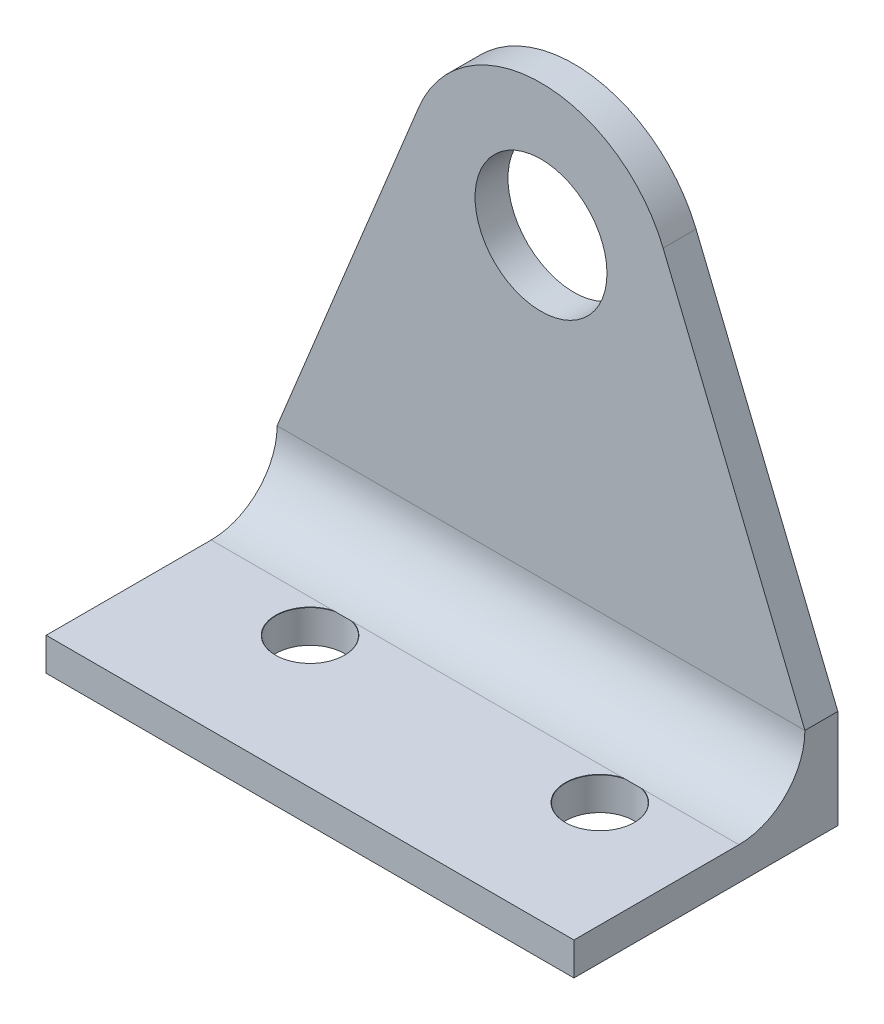
SolidWorks part; units mm, degrees
ref_plane "Front Plane" through (0, 0, 0) normal (0, 0, 1) x (1, 0, 0)
ref_plane "Top Plane" through (0, 0, 0) normal (0, 1, 0) x (1, 0, 0)
ref_plane "Right Plane" through (0, 0, 0) normal (1, 0, 0) x (0, 0, -1)
sketch "Sketch1" plane through (0, 0, 0) normal (1, 0, 0) x (0, 0, -1)
  line L0 (0, 0) -> (22.23, 0)
  line L1 (22.23, 0) -> (22.23, 47.63)
  line L2 (0, -3.17) -> (25.4, -3.17)
  line L3 (25.4, -3.17) -> (25.4, 47.63)
  line L4 (22.23, 47.63) -> (25.4, 47.63)
  line L5 (0, -3.17) -> (0, 0)
  dimension "D2" = 50.8
  dimension "D3" = 25.4
  dimension "D1" = 3.17
extrude "Boss-Extrude1" add sketch "Sketch1" along normal mid plane 50.8
fillet "Fillet1" radius 6.35 1 edges at (0, 0, -22.23)
sketch "Sketch2" plane through (0, 0, 0) normal (0, 1, 0) x (1, 0, 0)
  line L0 (-25.4, 15.88) -> (-25.4, 0) construction
  line L1 (25.4, 0) -> (-25.4, 0) construction
  point P0 (-12.7, 12.7)
  point P2 (15.1908, 12.7)
  point P9 (0, 0)
  point P10 (0, 0)
  dimension "D1" = 12.7
  dimension "D2" = 12.7
hole_wizard "M6 Clearance Hole1" positions "Sketch2" profile "Sketch3" hole size "M6" standard "ISO" end condition through all
sketch "Sketch3" plane through (-12.7, 0, -12.7) normal (1, 0, 0) x (0, 0, 1)
  line L0 (0, 0) -> (0, 3.17)
  line L1 (0, 3.17) -> (3.3, 3.17)
  line L2 (3.3, 3.17) -> (3.3, 0.025)
  line L3 (3.3, 0.025) -> (3.325, 0)
  line L5 (3.325, 0) -> (0, 0)
  line L6 (-3.3, 0.025) -> (-3.325, 0) construction
  line L11 (0, -6.35) -> (0, 107.95) construction
  dimension "Thru Hole Dia." = 6.6
  dimension "Thru Hole Depth" = 3.17
  dimension "Near C'Sink Dia." = 6.65
  dimension "Near C'Sink Angle" = 90
sketch "Sketch4" plane through (0, 0, -22.23) normal (0, 0, 1) x (1, 0, 0)
  line L0 (25.4, 47.63) -> (-25.4, 47.63) construction
  line L1 (-25.4, 6.35) -> (-11.7561, 39.7346)
  line L2 (25.4, 6.35) -> (11.7561, 39.7346)
  circle A0 centre (0, 34.93) radius 12.7
  circle A1 centre (0, 34.93) radius 6.35
  point P11 (0, 0)
  line M5 (-25.4, 47.63) -> (-25.4, 6.35)
  line M7 (25.4, 6.35) -> (25.4, 47.63)
  line M8 (25.4, 47.63) -> (-25.4, 47.63)
  dimension "D1" = 25.4
  dimension "D2" = 12.7
extrude "Cut-Extrude1" cut sketch "Sketch4" against normal through all contours A1 | A0 L2 M7 M8 | A0 L1 M8 M5
